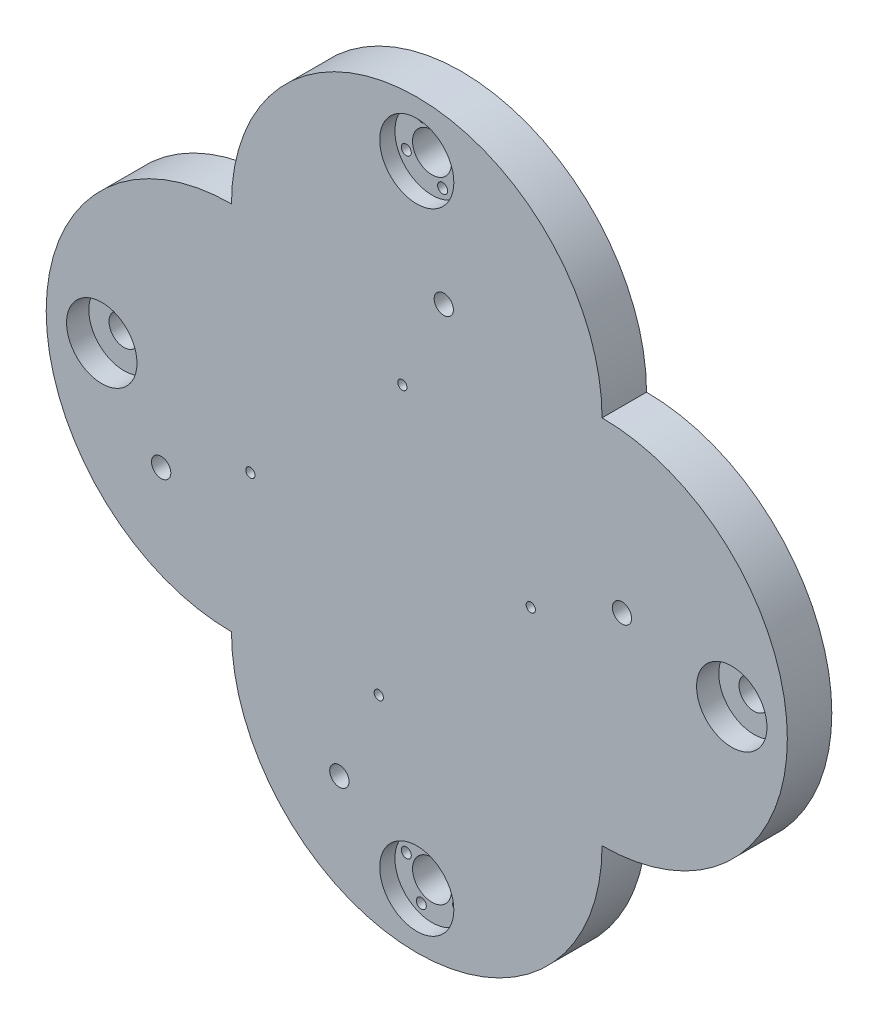
SolidWorks part; units mm, degrees
ref_plane "Ön Düzlem" through (0, 0, 0) normal (0, 0, 1) x (1, 0, 0)
ref_plane "Üst Düzlem" through (0, 0, 0) normal (0, 1, 0) x (1, 0, 0)
ref_plane "Sağ Düzlem" through (0, 0, 0) normal (1, 0, 0) x (0, 0, -1)
sketch "Çizim1" plane through (0, 0, 0) normal (0, 0, 1) x (1, 0, 0)
  line L0 (-74.0072, 59.5668) -> (25.9928, -40.4332)
  line L5 (25.9928, 59.5668) -> (-74.0072, -40.4332)
  arc A0 (25.9928, 59.5668) -> (-74.0072, 59.5668) centre (-24.0072, 59.5668) ccw
  arc A1 (25.9928, -40.4332) -> (25.9928, 59.5668) centre (25.9928, 9.5668) ccw
  arc A2 (-74.0072, -40.4332) -> (25.9928, -40.4332) centre (-24.0072, -40.4332) ccw
  arc A3 (-74.0072, 59.5668) -> (-74.0072, -40.4332) centre (-74.0072, 9.5668) ccw
  circle A4 centre (-24.0072, 94.5668) radius 4
  circle A5 centre (-109.0072, 9.5668) radius 4
  circle A6 centre (60.9928, 9.5668) radius 4
  circle A7 centre (-24.0072, -75.4332) radius 4
  dimension "D1" = 35
  dimension "D2" = 8
  dimension "D3" = 35
  dimension "D4" = 8
extrude "Yükseklik-Ekstrüzyon1" add sketch "Çizim1" along normal blind 12 contours L0 A3 L5 A5 | L5 A0 L0 A4 | L0 A1 L5 A6 | L5 A2 L0 A7
sketch "Çizim2" plane through (0, 0, 12) normal (0, 0, 1) x (1, 0, 0)
  circle A0 centre (-27.895, 40.3259) radius 1.25
  circle A1 centre (-68.9072, -0.6863) radius 1.25
  circle A2 centre (-34.259, -35.3345) radius 1.25
  circle A3 centre (6.7532, 5.6777) radius 1.25
extrude "Kes-Ekstrüzyon1" cut sketch "Çizim2" against normal blind 50
sketch "Çizim3" plane through (0, 0, 12) normal (0, 0, 1) x (1, 0, 0)
  line L0 (-124.0072, 9.5668) -> (75.9928, 9.5668)
  circle A0 centre (-24.0072, 94.5668) radius 10
  arc A1 (-74.0072, 59.5668) -> (-74.0072, -40.4332) centre (-74.0072, 9.5668) ccw construction
  arc A2 (25.9928, -40.4332) -> (25.9928, 59.5668) centre (25.9928, 9.5668) ccw construction
  circle A3 centre (-24.0072, -75.4332) radius 10
  circle M10 centre (-24.0072, -75.4332) radius 4
extrude "Kes-Ekstrüzyon2" cut sketch "Çizim3" against normal blind 4.1 contours A3 M10 | A0
sketch "Çizim4" plane through (0, 0, 7.9) normal (0, 0, 1) x (1, 0, 0)
  line L0 (-124.0072, 9.5668) -> (75.9928, 9.5668)
  circle A1 centre (-17.0793, 97.4397) radius 1.35
  circle A2 centre (-21.1344, 87.6388) radius 1.35
  circle A3 centre (-30.9352, 91.6939) radius 1.35
  circle A4 centre (-26.8801, 101.4947) radius 1.35
  arc A5 (-74.0072, 59.5668) -> (-74.0072, -40.4332) centre (-74.0072, 9.5668) ccw construction
  arc A6 (25.9928, -40.4332) -> (25.9928, 59.5668) centre (25.9928, 9.5668) ccw construction
  circle A13 centre (-24.0072, 94.5668) radius 5.25
  circle A14 centre (-24.0072, -75.4332) radius 5.25
  circle A15 centre (-26.8801, -82.3612) radius 1.35
  circle A16 centre (-30.9352, -72.5603) radius 1.35
  circle A17 centre (-21.1344, -68.5053) radius 1.35
  circle A18 centre (-17.0793, -78.3061) radius 1.35
  circle M1 centre (-24.0072, 94.5668) radius 4
extrude "Kes-Ekstrüzyon3" cut sketch "Çizim4" against normal blind 10 contours A15 | A18 | A16 | A17 | A14 | A2 | M1 | A3 | A13 M1 | A4 | A1
sketch "Çizim5" plane through (0, 0, 12) normal (0, 0, 1) x (1, 0, 0)
  circle A0 centre (-109.0072, 9.5668) radius 9.5
  circle A1 centre (60.9928, 9.5668) radius 9.5
  dimension "D1" = 19
  dimension "D2" = 19
extrude "Kes-Ekstrüzyon4" cut sketch "Çizim5" against normal blind 50
sketch "Çizim6" plane through (0, 0, 0) normal (0, 0, -1) x (-1, 0, 0)
  circle A0 centre (109.0072, 9.5668) radius 9.5
  circle A1 centre (-60.9928, 9.5668) radius 9.5
  circle A2 centre (-60.9928, 9.5668) radius 4.05
  circle A3 centre (109.0072, 9.5668) radius 4.05
  dimension "D1" = 8.1
extrude "Yükseklik-Ekstrüzyon2" add sketch "Çizim6" against normal blind 6
sketch "Çizim7" plane through (0, 0, 12) normal (0, 0, 1) x (1, 0, 0)
  circle A0 centre (-16.7171, 64.7627) radius 2.6
  circle A1 centre (31.3662, 16.6795) radius 2.6
  circle A4 centre (-92.98, -11.5002) radius 2.6
  circle A5 centre (-44.8968, -59.5834) radius 2.6
extrude "Kes-Ekstrüzyon5" cut sketch "Çizim7" against normal blind 50
